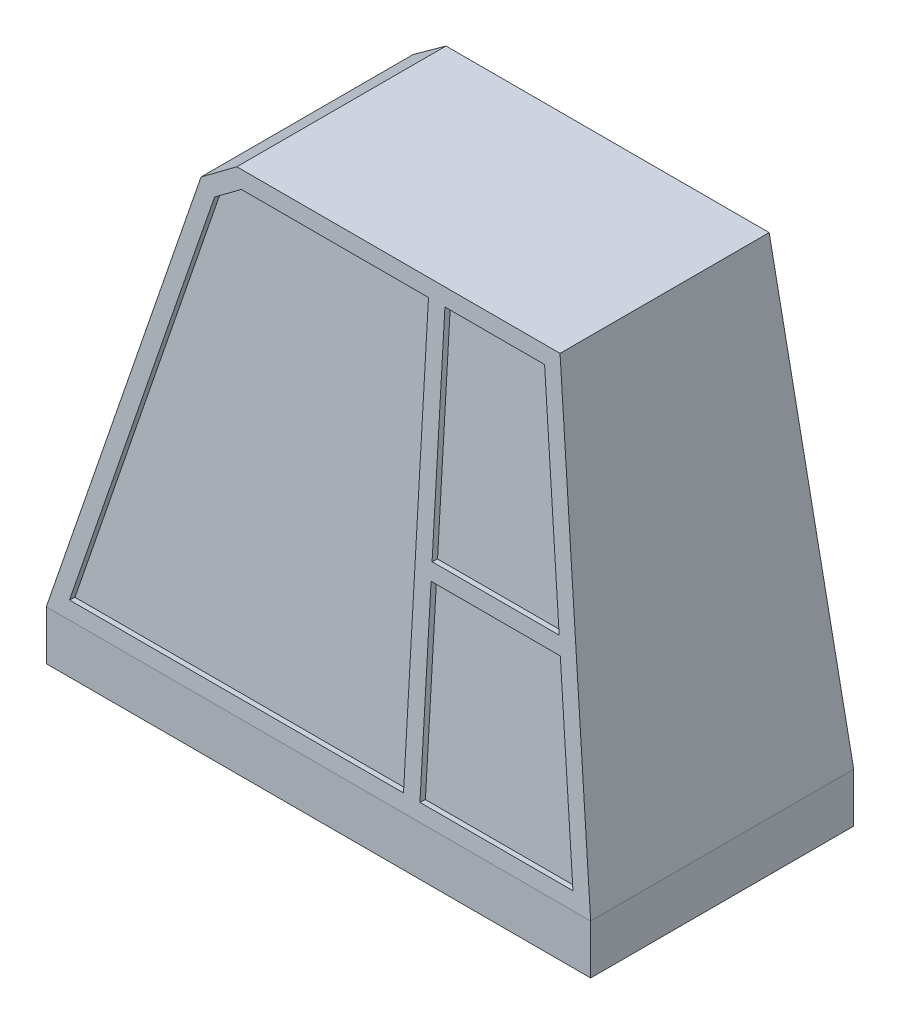
SolidWorks part; units mm, degrees
ref_plane "Front Plane" through (0, 0, 0) normal (0, 0, 1) x (1, 0, 0)
ref_plane "Top Plane" through (0, 0, 0) normal (0, 1, 0) x (1, 0, 0)
ref_plane "Right Plane" through (0, 0, 0) normal (1, 0, 0) x (0, 0, -1)
sketch "Sketch2" plane through (0, 0, 0) normal (0, 0, 1) x (1, 0, 0)
  line L0 (0, 228.6) -> (599.2484, 2194.4019)
  line L1 (0, 0) -> (2522.982, 0)
  line L2 (0, 0) -> (0, 228.6)
  line L3 (758.163, 2311.4) -> (2256.1893, 2311.4)
  line L4 (2522.982, 0) -> (2522.982, 228.6)
  line L5 (599.2484, 2194.4019) -> (758.163, 2311.4)
  line L6 (2522.982, 228.6) -> (2256.1893, 2311.4)
  line L7 (0, 228.6) -> (2522.982, 228.6) construction
  dimension "D1" = 2522.982
  dimension "D3" = 228.6
extrude "Boss-Extrude1" add sketch "Sketch2" along normal blind 1219.2
sketch "Sketch3" plane through (2522.982, 0, 0) normal (1, 0, 0) x (0, 0, -1)
  line L0 (-1219.2, 228.6) -> (-1094.2926, 2311.4)
  line L1 (-1219.2, 2311.4) -> (0, 2311.4)
  line L2 (-1219.2, 2311.4) -> (-1219.2, 0)
  line L3 (-1219.2, 0) -> (0, 0)
  line L4 (0, 2311.4) -> (0, 0)
  line L5 (-609.6, 0) -> (-609.6, 2311.4) construction
  line L6 (0, 228.6) -> (-124.9074, 2311.4)
extrude "Cut-Extrude1" cut sketch "Sketch3" against normal through all contours L1 L2 L0 | L6 L4 L1
sketch "Sketch4" plane through (-63.7607, 19.4366, 0) normal (-0.9565, 0.2916, 0) x (0, 0, 1)
  line L0 (1029.355, 2197.5755) -> (1138.5035, 294.8659)
  line L1 (189.845, 2197.5755) -> (1029.355, 2197.5755)
  line L6 (189.845, 2197.5755) -> (80.6965, 294.8659)
  line L8 (0, 218.6659) -> (117.8909, 2273.7755) construction
  line L9 (1219.2, 218.6659) -> (1101.3091, 2273.7755) construction
  line L10 (80.6965, 294.8659) -> (1138.5035, 294.8659)
  line L11 (1101.3091, 2273.7755) -> (117.8909, 2273.7755) construction
  line L13 (1219.2, 218.6659) -> (0, 218.6659) construction
  dimension "D1" = 76.2
  dimension "D2" = 76.2
  dimension "D3" = 76.2
  dimension "D4" = 76.2
extrude "Cut-Extrude2" cut sketch "Sketch4" against normal blind 25.4
sketch "Sketch5" plane through (0, 73.6737, 1228.4911) normal (0, 0.0599, 0.9982) x (1, 0, 0)
  line L0 (664.798, 2078.2008) -> (783.2243, 2165.5467)
  line L1 (783.2243, 2165.5467) -> (1651, 2165.5467)
  line L2 (2189.1121, 2165.5467) -> (2316.2975, 1170.8505)
  line L3 (2436.4184, 231.4046) -> (1727.2, 231.4046)
  line L4 (102.8366, 231.4046) -> (664.798, 2078.2008)
  line L5 (0, 155.2046) -> (599.2484, 2124.5384) construction
  line L6 (599.2484, 2124.5384) -> (758.163, 2241.7467) construction
  line L7 (2326.0407, 1094.6505) -> (2436.4184, 231.4046)
  line L8 (2256.1893, 2241.7467) -> (2522.982, 155.2046) construction
  line L9 (0, 155.2046) -> (2522.982, 155.2046) construction
  line L10 (758.163, 2241.7467) -> (2256.1893, 2241.7467) construction
  line L11 (1651, 2165.5467) -> (1651, 231.4046)
  line L12 (1727.2, 231.4046) -> (1727.2, 1094.6505)
  line L13 (1727.2, 1170.8505) -> (2316.2975, 1170.8505)
  line L14 (1727.2, 1094.6505) -> (2326.0407, 1094.6505)
  line L15 (1727.2, 1170.8505) -> (1727.2, 2165.5467)
  line L16 (1727.2, 2165.5467) -> (2189.1121, 2165.5467)
  line L17 (1651, 231.4046) -> (102.8366, 231.4046)
  line L18 (0, 155.2046) -> (0, -72.9854) construction
  point P20 (2316.2975, 1170.8505)
  dimension "D1" = 76.2
  dimension "D2" = 76.2
  dimension "D3" = 76.2
  dimension "D4" = 76.2
  dimension "D5" = 76.2
  dimension "D6" = 76.2
  dimension "D7" = 76.2
  dimension "D8" = 1651
extrude "Cut-Extrude3" cut sketch "Sketch5" against normal blind 25.4 contours L2 L13 L15 L16 | L3 L12 L14 L7 | L4 L0 L1 L11 L17
sketch "Sketch6" plane through (0, 0.8192, -13.6602) normal (0, 0.0599, -0.9982) x (-1, 0, 0)
  line L0 (-2189.1121, 2238.5321) -> (-2312.7653, 1271.461)
  line L1 (-2436.4184, 304.39) -> (-1727.2, 304.39)
  line L2 (-102.8366, 304.39) -> (-664.798, 2151.1861)
  line L3 (-664.798, 2151.1861) -> (-783.2243, 2238.5321)
  line L4 (-783.2243, 2238.5321) -> (-1651, 2238.5321)
  line L5 (-758.163, 2314.7321) -> (-2256.1893, 2314.7321) construction
  line L6 (-2256.1893, 2314.7321) -> (-2522.982, 228.19) construction
  line L7 (0, 228.19) -> (-2522.982, 228.19) construction
  line L8 (0, 228.19) -> (-599.2484, 2197.5237) construction
  line L9 (-599.2484, 2197.5237) -> (-758.163, 2314.7321) construction
  line L10 (-1727.2, 2238.5321) -> (-1727.2, 1271.461)
  line L11 (-1651, 2238.5321) -> (-1651, 304.39)
  line L12 (-1727.2, 1271.461) -> (-2312.7653, 1271.461)
  line L13 (-1727.2, 1195.261) -> (-2322.5085, 1195.261)
  line L14 (0, 228.19) -> (0, 0) construction
  line L15 (-2322.5085, 1195.261) -> (-2436.4184, 304.39)
  line L16 (-1727.2, 1195.261) -> (-1727.2, 304.39)
  line L17 (-1651, 304.39) -> (-102.8366, 304.39)
  line L18 (-1727.2, 2238.5321) -> (-2189.1121, 2238.5321)
  point P25 (0, 114.095)
  dimension "D1" = 76.2
  dimension "D2" = 76.2
  dimension "D3" = 76.2
  dimension "D4" = 76.2
  dimension "D5" = 76.2
  dimension "D6" = 76.2
  dimension "D7" = 76.2
  dimension "D8" = 1651
extrude "Cut-Extrude4" cut sketch "Sketch6" against normal blind 25.4
